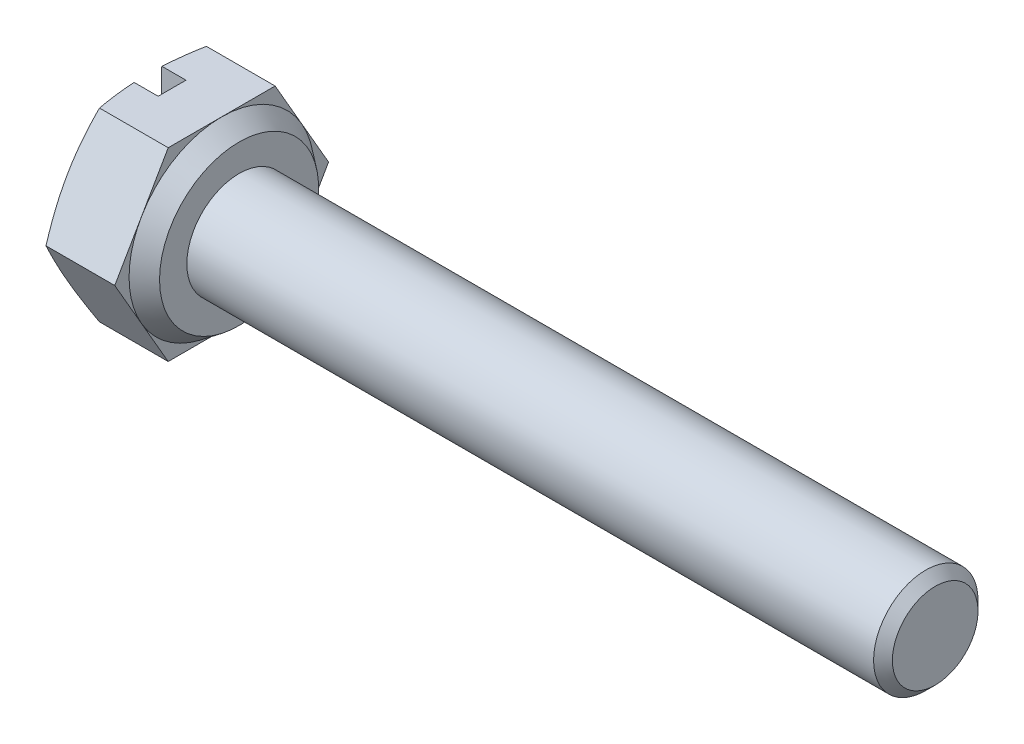
SolidWorks part; units mm, degrees
ref_plane "Front" through (0, 0, 0) normal (0, 0, 1) x (1, 0, 0)
ref_plane "Top" through (0, 0, 0) normal (0, 1, 0) x (1, 0, 0)
ref_plane "Right" through (0, 0, 0) normal (1, 0, 0) x (0, 0, -1)
other "Configuration Table"
sketch "Sketch-BaseHead" plane through (0, 0, 0) normal (1, 0, 0) x (0, 0, -1)
  line L1 (1.5358, -2.66) -> (3.0715, 0)
  line L2 (3.0715, 0) -> (1.5358, 2.66)
  line L3 (1.5358, 2.66) -> (-1.5358, 2.66)
  line L4 (-1.5358, 2.66) -> (-3.0715, 0)
  line L5 (-3.0715, 0) -> (-1.5358, -2.66)
  line L6 (-1.5358, -2.66) -> (1.5358, -2.66)
  circle A0 centre (0, 0) radius 2.66 construction
extrude "BaseHead" add sketch "Sketch-BaseHead" along normal blind 2.125
ref_plane "Plane1" through (2.525, 0, 0) normal (1, 0, 0) x (0, 0, -1)
sketch "Sketch1" plane through (0, 0, 0) normal (0, 0, 1) x (1, 0, 0)
  line L0 (2.125, 0) -> (2.625, 0)
  line L1 (2.625, 0) -> (2.625, -2.285)
  line L2 (2.625, -2.285) -> (2.125, -2.66)
  line L3 (2.125, -2.66) -> (2.125, 0)
revolve "Revolve1" add sketch "Sketch1" angle 360 about axis through (-4.0016, 0, 0) along (1, 0, 0)
sketch "Sketch3" plane through (2.625, 0, 0) normal (1, 0, 0) x (0, 0, -1)
  circle A0 centre (0, 0) radius 1.5
extrude "BaseBody" add sketch "Sketch3" along normal blind 20
cosmetic thread "ThreadCosmetic1" [suppressed] parameters "D2"=2.459
chamfer "Chamfer1" distance 0.2705 angle 45 1 edges at (22.625, 0, -1.5)
fillet "HeadFillet" [suppressed] radius 0.1
sketch "Sketch4" plane through (-0.2646, 0, 5.9169) normal (0, 1, 0) x (0, 0, -1)
  line L0 (5.9169, 3.7369) -> (5.9169, -10.4477) construction
  line L2 (8.9884, -0.2646) -> (8.5769, -0.2646)
  line L4 (8.5769, -0.2646) -> (8.9884, -0.4144)
  line L6 (8.9884, -0.4144) -> (8.9884, -0.2646)
revolve "HeadChamfer" cut sketch "Sketch4" angle 360 about L0
sketch "Sketch5" plane through (0, 0, 0) normal (0, 1, 0) x (1, 0, 0)
  line L0 (0, 0.4) -> (0, -0.4)
  line L1 (0.7, -0.4) -> (0.7, 0.4)
  line L2 (0.7, 0.4) -> (0, 0.4)
  line L3 (0, -0.4) -> (0.7, -0.4)
  dimension "n" = 0.8
  dimension "t" = 0.7
extrude "Slot" cut sketch "Sketch5" against normal through all and the other way through all
sketch "Sketch6" plane through (0, 0, 0) normal (0, 0, 1) x (1, 0, 0)
  line L0 (2.625, 1.7) -> (2.8955, 1.7)
  line L1 (2.8955, 1.7) -> (2.8955, 1.5)
  line L2 (2.8955, 1.5) -> (2.7603, 1.2657)
  line L3 (2.625, 1.5) -> (2.7603, 1.2657)
  line L4 (2.625, 1.7) -> (2.625, 1.5)
  line L5 (14.0487, 0) -> (0, 0) construction
  line L6 (2.625, 1.5) -> (2.8955, 1.5) construction
  line L7 (2.7603, 1.5) -> (2.7603, 1.2657) construction
  point P5 (2.7603, 1.7)
revolve "Cut-Revolve10" [suppressed] cut sketch "Sketch6" angle 360 about L5
pattern_linear "LPattern10" [suppressed] count 62 spacing 0.3246
equation "\"D1@Sketch1\" = \"s@Sketch-BaseHead\"/ 2 "
equation "\"D2@Sketch4\" = \"s@Sketch-BaseHead\""
equation "\"D1@Chamfer1\" =  ( \"d@Sketch3\" - \"D2@ThreadCosmetic1\" ) / 2 "
equation "\"D2@Sketch6\" = (  \"d@Sketch3\" - \"D2@ThreadCosmetic1\" )  / 2"
equation "\"D3@LPattern10\" = \"D2@Sketch6\" * 1.2"
equation "\"D1@LPattern10\" = \"l@BaseBody\" / \"D3@LPattern10\""
